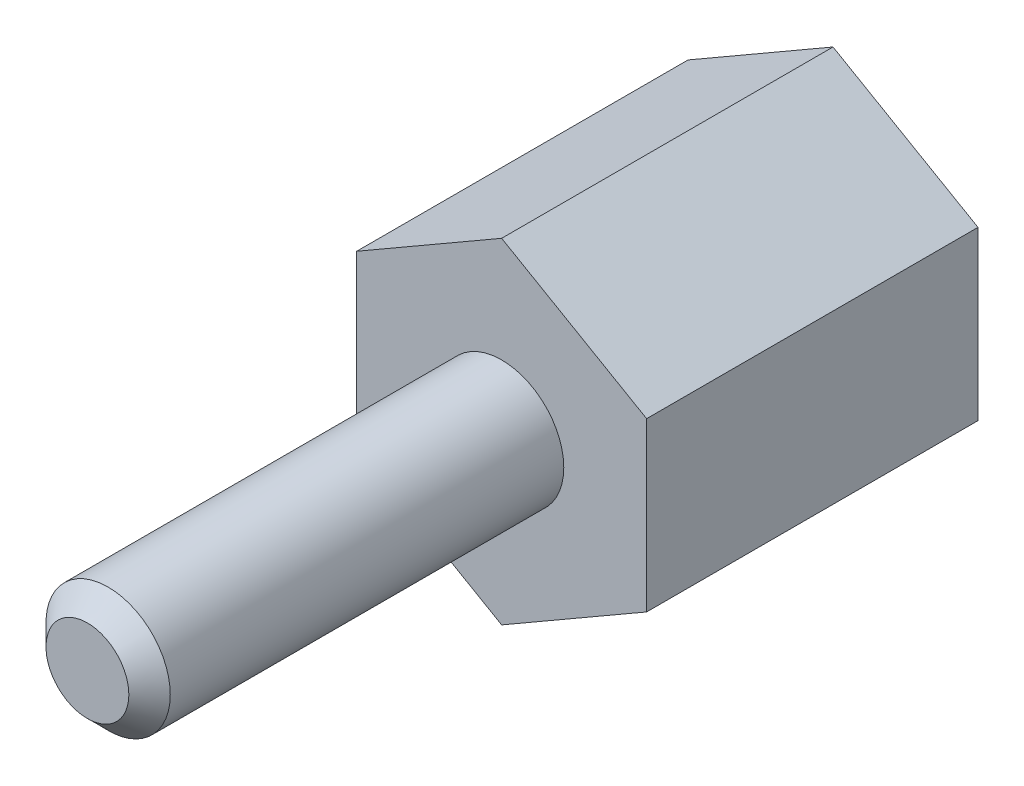
SolidWorks part; units mm, degrees
ref_plane "Спереди" through (0, 0, 0) normal (0, 0, 1) x (1, 0, 0)
ref_plane "Сверху" through (0, 0, 0) normal (0, 1, 0) x (1, 0, 0)
ref_plane "Справа" through (0, 0, 0) normal (1, 0, 0) x (0, 0, -1)
sketch "Эскиз1" plane through (0, 0, 0) normal (0, 0, 1) x (1, 0, 0)
  line L1 (0, 4.0415) -> (-3.5, 2.0207)
  line L2 (-3.5, 2.0207) -> (-3.5, -2.0207)
  line L3 (-3.5, -2.0207) -> (0, -4.0415)
  line L4 (0, -4.0415) -> (3.5, -2.0207)
  line L5 (3.5, -2.0207) -> (3.5, 2.0207)
  line L6 (3.5, 2.0207) -> (0, 4.0415)
  circle A0 centre (0, 0) radius 3.5 construction
  dimension "D1" = 7
extrude "Вытянуть1" add sketch "Эскиз1" along normal blind 8
sketch "Эскиз2" plane through (0, 0, 8) normal (0, 0, 1) x (1, 0, 0)
  circle A0 centre (0, 0) radius 1.5
  dimension "D1" = 3
extrude "Вытянуть2" add sketch "Эскиз2" along normal blind 10
hole_wizard "Сверление под метчик M3x0.51" positions "Трехмерный эскиз1" profile "Эскиз3" hole size "M3x0.5" standard "Ansi Метрический"
sketch3d "Трехмерный эскиз1"
  point P0 (0, 0, 0)
sketch "Эскиз3" plane through (0, 0, 0) normal (1, 0, 0) x (0, 1, 0)
  line L0 (0, 0) -> (0, 6.7511)
  line L1 (0, 6.7511) -> (1.25, 6)
  line L2 (1.25, 6) -> (1.25, 0.25)
  line L3 (1.25, 0.25) -> (1.5, 0)
  line L5 (1.5, 0) -> (0, 0)
  line L6 (-1.25, 0.25) -> (-1.5, 0) construction
  line L10 (0, 6.7511) -> (-1.25, 6) construction
  line L11 (0, -6.35) -> (0, 107.95) construction
  dimension "Диаметр отверстия" = 2.5
  dimension "Глубина отверстия" = 6
  dimension "Диаметр передней зенковки" = 3
  dimension "Угол передней зенковки" = 90
  dimension "Угол заточки сверла" = 118
chamfer "Фаска1" distance 0.5 angle 45
